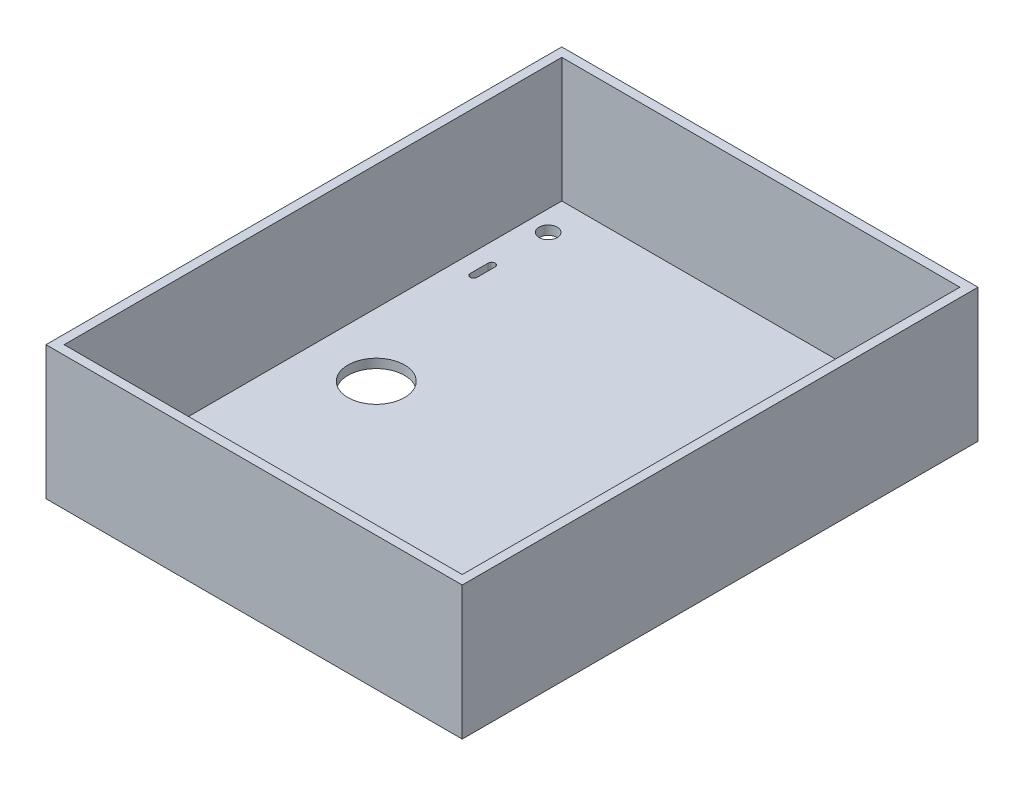
SolidWorks part; units mm, degrees
ref_plane "Front Plane" through (0, 0, 0) normal (0, 0, 1) x (1, 0, 0)
ref_plane "Top Plane" through (0, 0, 0) normal (0, 1, 0) x (1, 0, 0)
ref_plane "Right Plane" through (0, 0, 0) normal (1, 0, 0) x (0, 0, -1)
sketch "Sketch1" plane through (0, 0, 0) normal (0, 1, 0) x (1, 0, 0)
  line L1 (-92, 114) -> (92, 114)
  line L2 (-92, 114) -> (-92, -114)
  line L3 (-92, -114) -> (92, -114)
  line L4 (92, 114) -> (92, -114)
  line L5 (-92, 114) -> (92, -114) construction
  line L6 (-92, -114) -> (92, 114) construction
  point P0 (0, 0)
  dimension "D1" = 228
  dimension "D2" = 184
extrude "Boss-Extrude1" add sketch "Sketch1" along normal blind 59
sketch "Sketch2" plane through (0, 59, 0) normal (0, 1, 0) x (1, 0, 0)
  line L0 (92, 114) -> (-92, 114) construction
  line L1 (-88, 110) -> (88, 110)
  line L2 (-88, 110) -> (-88, -110)
  line L3 (-88, -110) -> (88, -110)
  line L4 (88, 110) -> (88, -110)
  line L5 (-88, 110) -> (88, -110) construction
  line L6 (-88, -110) -> (88, 110) construction
  point P0 (0, 0)
  dimension "D1" = 4
  dimension "D2" = 4
extrude "Cut-Extrude1" cut sketch "Sketch2" against normal blind 55
sketch "Sketch4" plane through (0, 4, 0) normal (0, 1, 0) x (1, 0, 0)
  line L0 (-79, 70) -> (-79, 62) construction
  line L1 (-77.5, 70) -> (-77.5, 62)
  line L2 (-80.5, 70) -> (-80.5, 62)
  line L3 (-79, -62) -> (-79, -70) construction
  line L8 (-77.5, -62) -> (-77.5, -70)
  line L9 (-80.5, -62) -> (-80.5, -70)
  line L10 (79, -62) -> (79, -70) construction
  line L11 (77.5, 70) -> (77.5, 62) construction
  line L12 (80.5, -62) -> (80.5, -70)
  line L13 (77.5, -62) -> (77.5, -70)
  line L15 (79, 70) -> (79, 62)
  line L16 (76, 70) -> (76, 62)
  circle A0 centre (-79, -95) radius 4
  circle A4 centre (-79, 95) radius 4
  circle A5 centre (79, -95) radius 4
  circle A6 centre (79, 95) radius 4
  arc A7 (-77.5, 70) -> (-80.5, 70) centre (-79, 70) ccw
  arc A8 (-80.5, 62) -> (-77.5, 62) centre (-79, 62) ccw
  arc A13 (-77.5, -62) -> (-80.5, -62) centre (-79, -62) ccw
  arc A14 (-80.5, -70) -> (-77.5, -70) centre (-79, -70) ccw
  arc A15 (80.5, -62) -> (77.5, -62) centre (79, -62) ccw
  arc A16 (77.5, -70) -> (80.5, -70) centre (79, -70) ccw
  arc A17 (79, 70) -> (76, 70) centre (77.5, 70) ccw
  arc A18 (76, 62) -> (79, 62) centre (77.5, 62) ccw
  point P3 (-79, 66)
  point P20 (-79, -66)
  point P32 (79, -66)
  point P39 (77.5, 66)
  dimension "D4" = 9
  dimension "D10" = 15
  dimension "D16" = 44
  dimension "D1" = 15
  dimension "D2" = 9
  dimension "D3" = 4
  dimension "D5" = 15
  dimension "D6" = 4
  dimension "D7" = 9
  dimension "D8" = 15
  dimension "D9" = 4
  dimension "D11" = 9
  dimension "D12" = 4
  dimension "D13" = 44
  dimension "D14" = 8
  dimension "D15" = 3
  dimension "D17" = 8
  dimension "D18" = 3
  dimension "D19" = 44
  dimension "D20" = 8
  dimension "D21" = 3
  dimension "D22" = 44
  dimension "D23" = 8
  dimension "D24" = 3
extrude "Cut-Extrude2" cut sketch "Sketch4" against normal through all
sketch "Sketch6" plane through (0, 4, 0) normal (0, 1, 0) x (1, 0, 0)
  circle A0 centre (-60, 0) radius 12.5
  circle A1 centre (0, -80) radius 12.5
  point P6 (0, -74.4837)
  dimension "D1" = 110
  dimension "D2" = 25
  dimension "D5" = 25
  dimension "D3" = 60
  dimension "D4" = 80
  dimension "D6" = 88
extrude "Cut-Extrude3" cut sketch "Sketch6" against normal through all
